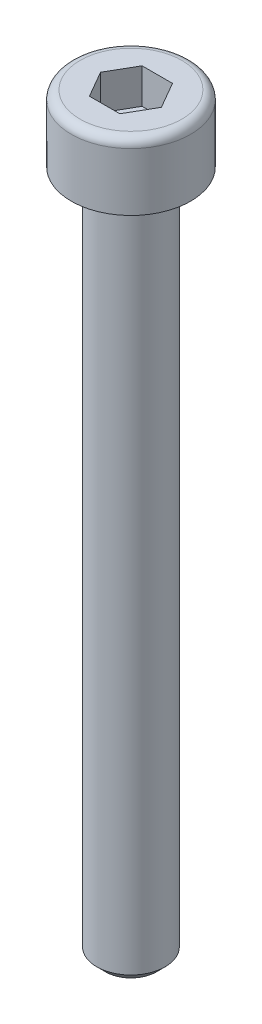
SolidWorks part; units mm, degrees
material "1023 Tôle d'acier au carbone (SS)"
ref_plane "Plan de face" through (0, 0, 0) normal (0, 0, 1) x (1, 0, 0)
ref_plane "Plan de dessus" through (0, 0, 0) normal (0, 1, 0) x (1, 0, 0)
ref_plane "Plan de droite" through (0, 0, 0) normal (1, 0, 0) x (0, 0, -1)
sketch "Esquisse1" plane through (0, 0, 0) normal (0, 0, 1) x (1, 0, 0)
  line L0 (0, 3.8) -> (0, -39) construction
  line L1 (0, 3.8) -> (-2.9, 3.8)
  line L2 (-3.4, 3.3) -> (-3.4, 0)
  line L3 (-3.4, 0) -> (-1.95, 0)
  line L4 (-1.95, 0) -> (-1.95, -38.5)
  line L5 (-1.95, -38.5) -> (-1.45, -39)
  line L6 (-1.45, -39) -> (0, -39)
  line L7 (0, 3.8) -> (0, -39)
  arc A0 (-2.9, 3.8) -> (-3.4, 3.3) centre (-2.9, 3.3) ccw
  point P11 (-1.95, -39)
  dimension "D5" = 0.5
  dimension "D1" = 3.9
  dimension "D2" = 6.8
  dimension "D3" = 39
  dimension "D4" = 3.8
  dimension "D8" = 0.5
revolve "Révolution1" add sketch "Esquisse1" angle 360 about L0
cosmetic thread "Représentation de filetage1" parameters "D2"=3.2
sketch "Esquisse2" plane through (0, 3.8, 0) normal (0, 1, 0) x (-1, 0, 0)
  line L1 (-1.7321, 0) -> (-0.866, -1.5)
  line L2 (-0.866, -1.5) -> (0.866, -1.5)
  line L3 (0.866, -1.5) -> (1.7321, 0)
  line L4 (1.7321, 0) -> (0.866, 1.5)
  line L5 (0.866, 1.5) -> (-0.866, 1.5)
  line L6 (-0.866, 1.5) -> (-1.7321, 0)
  circle A0 centre (0, 0) radius 1.5 construction
  dimension "D1" = 3
extrude "Enlèv. mat.-Extru.1" cut sketch "Esquisse2" against normal blind 2
